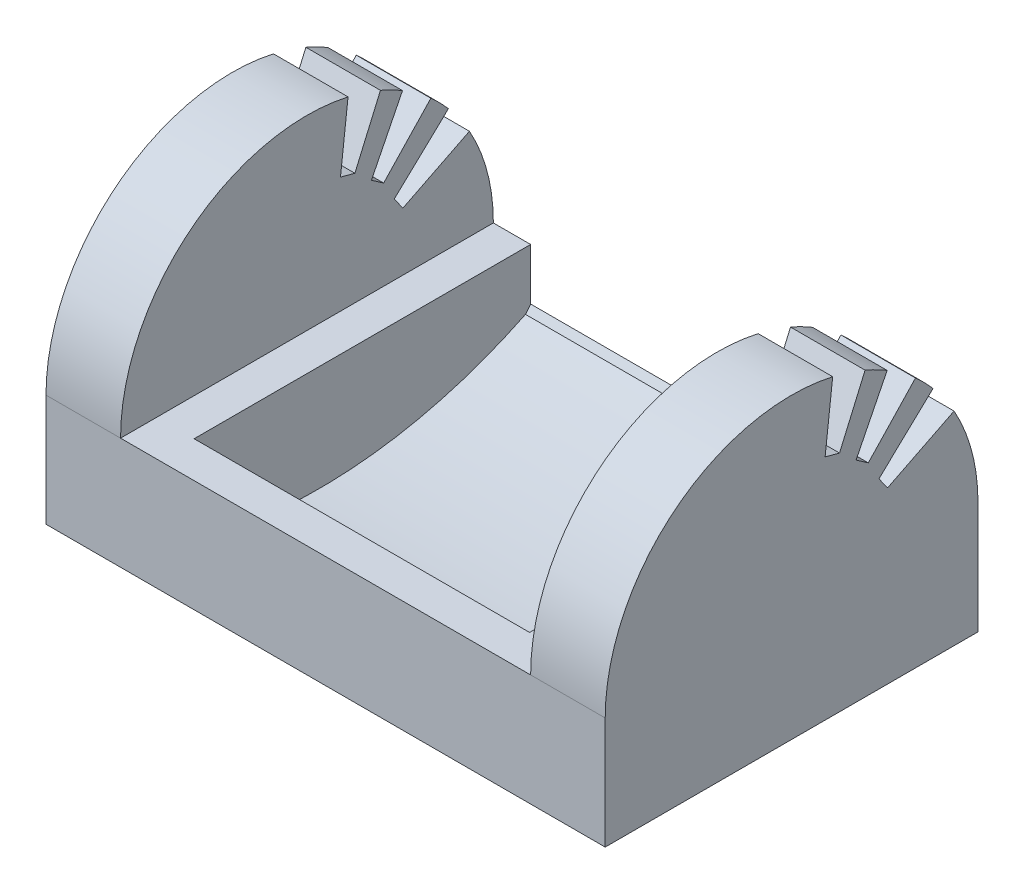
SolidWorks part; units mm, degrees
ref_plane "Front Plane" through (0, 0, 0) normal (0, 0, 1) x (1, 0, 0)
ref_plane "Top Plane" through (0, 0, 0) normal (0, 1, 0) x (1, 0, 0)
ref_plane "Right Plane" through (0, 0, 0) normal (1, 0, 0) x (0, 0, -1)
sketch "Sketch1" plane through (0, 0, 0) normal (0, 1, 0) x (1, 0, 0)
  line L1 (0, 0) -> (150, 0)
  line L2 (0, 0) -> (0, 100)
  line L3 (0, 100) -> (150, 100)
  line L4 (150, 0) -> (150, 100)
  dimension "D1" = 150
  dimension "D2" = 100
extrude "Boss-Extrude1" add sketch "Sketch1" along normal blind 30
sketch "Sketch3" plane through (0, 30, 0) normal (0, 1, 0) x (1, 0, 0)
  line L0 (150, 50) -> (0, 50) construction
  line L1 (150, 0) -> (150, 100) construction
  line L2 (0, 100) -> (0, 0) construction
  line L3 (75, 100) -> (75, 0) construction
  line L4 (150, 100) -> (130, 100)
  line L5 (150, 100) -> (150, 50)
  line L6 (150, 50) -> (130, 50)
  line L7 (130, 100) -> (130, 50)
  line L8 (150, 100) -> (0, 100) construction
  line L9 (0, 0) -> (150, 0) construction
  line L10 (20, 100) -> (20, 50)
  line L11 (0, 50) -> (20, 50)
  line L12 (0, 100) -> (0, 50)
  line L13 (0, 100) -> (20, 100)
  dimension "D1" = 20
revolve "Revolve1" add sketch "Sketch3" angle 180 about L0
sketch "Sketch4" plane through (150, 0, 0) normal (1, 0, 0) x (0, 0, -1)
  line L0 (0, 0) -> (100, 0) construction
  line L1 (94.0568, 54.745) -> (88.321, 62.9365)
  line L3 (75.7242, 45.5707) -> (73.4299, 48.8474)
  line L5 (91.1889, 58.8408) -> (21.8337, 10.2777) construction
  line L6 (88.321, 62.9365) -> (73.4299, 48.8474)
  line L7 (0, 30) -> (100, 30) construction
  line L8 (0, 30) -> (0, 0) construction
  line L9 (100, 30) -> (100, 0) construction
  line L11 (75.7242, 45.5707) -> (94.0568, 54.745)
  arc A0 (100, 30) -> (0, 30) centre (50, 30) ccw construction
  point P14 (50, 30)
  point P22 (73.1368, 49.2896)
  dimension "D1" = 35
  dimension "D2" = 10
  dimension "D3" = 2
  dimension "D4" = 30
  dimension "D5" = 30.0697
  dimension "D6" = 2
  dimension "D7" = 20.5
extrude "Cut-Extrude2" cut sketch "Sketch4" against normal through all
pattern_circular "CirPattern1" count 3 every 20 about axis through (0, 35.1631, -49.3094) along (1, 0, 0) of "Cut-Extrude2"
sketch "Sketch8" plane through (150, 0, 0) normal (1, 0, 0) x (0, 0, -1)
  line L1 (111.1933, 30) -> (9.7334, 30)
  line L2 (111.1933, 30) -> (98.6151, 14.4504)
  line L5 (9.7334, 30) -> (9.7334, 6.1636)
  arc A0 (9.7334, 6.1636) -> (98.6151, 14.4504) centre (43.2339, 127.6503) ccw
  point P3 (3.7371, 29.184)
  point P4 (89.0291, 10)
  point P5 (111.1933, 28.8318)
  point P7 (0, 0)
  point P8 (0, 0)
  point P9 (0, 0)
  point P12 (0, 0)
  point P13 (9.7334, 10.2294)
  point P14 (0, 0)
  point P15 (9.7334, 30)
  point P16 (9.7334, 6.1636)
  dimension "D1" = 20
extrude "Cut-Extrude3" cut sketch "Sketch8" along direction (1, 0, 0) on the side against the normal blind 90 from offset 30
